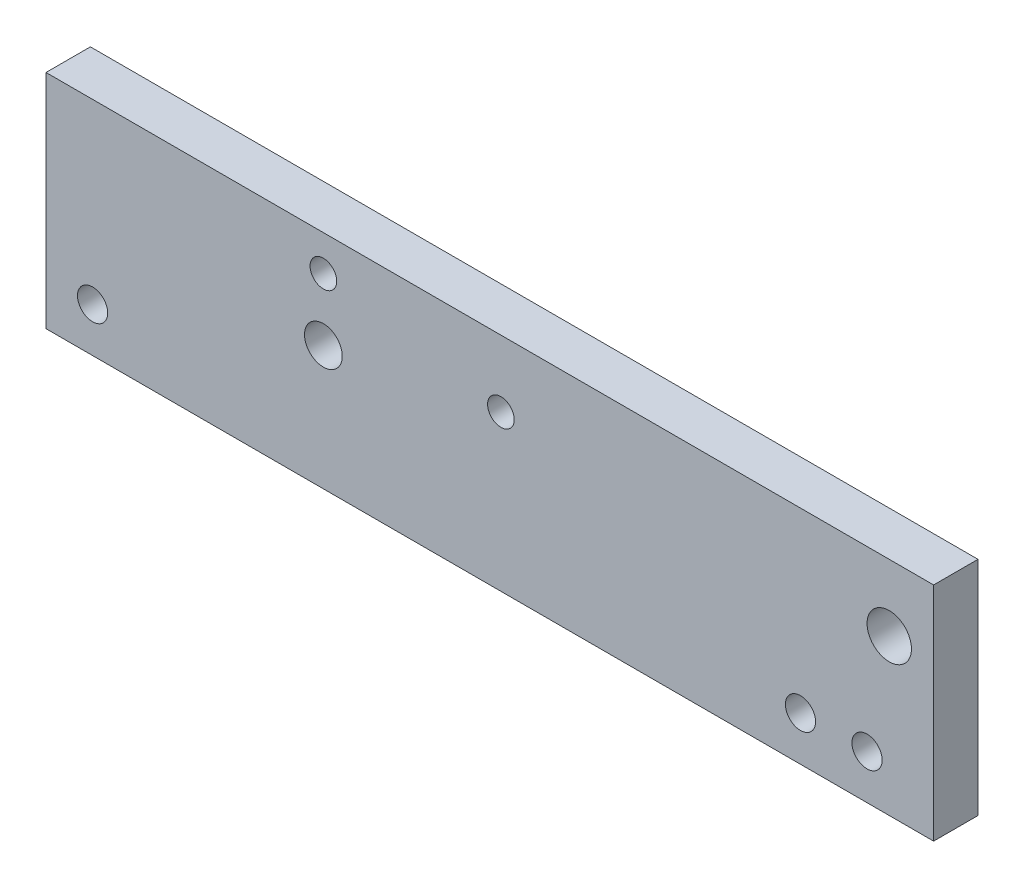
SolidWorks part; units mm, degrees
ref_plane "Front Plane" through (0, 0, 0) normal (0, 0, 1) x (1, 0, 0)
ref_plane "Top Plane" through (0, 0, 0) normal (0, 1, 0) x (1, 0, 0)
ref_plane "Right Plane" through (0, 0, 0) normal (1, 0, 0) x (0, 0, -1)
sketch "Sketch1" plane through (0, 0, 0) normal (0, 0, 1) x (1, 0, 0)
  line L1 (100, -25) -> (-100, -25)
  line L2 (100, -25) -> (100, 25)
  line L3 (100, 25) -> (-100, 25)
  line L4 (-100, -25) -> (-100, 25)
  line L5 (100, -25) -> (-100, 25) construction
  line L6 (100, 25) -> (-100, -25) construction
  point P0 (0, 0)
  dimension "D1" = 200
  dimension "D2" = 50
extrude "Boss-Extrude1" add sketch "Sketch1" along normal blind 10
sketch "Sketch2" plane through (0, 0, 10) normal (0, 0, 1) x (1, 0, 0)
  line L0 (100, -25) -> (100, 25) construction
  line L1 (100, 25) -> (-100, 25) construction
  circle A0 centre (90, 10) radius 5
  circle A1 centre (2.5, 10) radius 3
  circle A2 centre (-37.5, 17) radius 3
  circle A3 centre (-37.5, 3) radius 4.25
  dimension "D1" = 10
  dimension "D3" = 15
  dimension "D5" = 40
  dimension "D9" = 6
  dimension "D2" = 15
  dimension "D4" = 87.5
  dimension "D6" = 40
  dimension "D7" = 8
  dimension "D8" = 14
extrude "Cut-Extrude1" cut sketch "Sketch2" against normal through all
cosmetic thread "Cosmetic Thread4"
sketch "Sketch3" plane through (0, 0, 10) normal (0, 0, 1) x (1, 0, 0)
  line L0 (-100, -25) -> (100, -25) construction
  line L1 (-100, 25) -> (-100, -25) construction
  line L2 (100, -25) -> (100, 25) construction
  circle A0 centre (-89.5, -15) radius 3.4
  circle A1 centre (70, -15) radius 3.4
  circle A2 centre (85, -15) radius 3.4
  dimension "D1" = 6.8
  dimension "D2" = 6.8
  dimension "D3" = 6.8
  dimension "D4" = 10
  dimension "D5" = 10.5
  dimension "D6" = 15
  dimension "D7" = 10
  dimension "D8" = 15
extrude "Cut-Extrude2" cut sketch "Sketch3" against normal through all
cosmetic thread "Cosmetic Thread1" parameters "D2"=8
cosmetic thread "Cosmetic Thread2" parameters "D2"=8
cosmetic thread "Cosmetic Thread3" parameters "D2"=8
